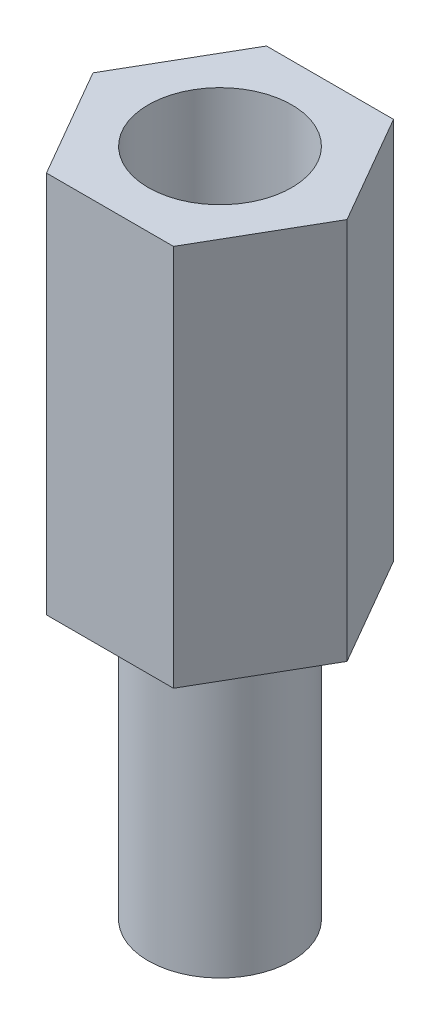
SolidWorks part; units mm, degrees
material "Brass"
ref_plane "Front Plane" through (0, 0, 0) normal (0, 0, 1) x (1, 0, 0)
ref_plane "Top Plane" through (0, 0, 0) normal (0, 1, 0) x (1, 0, 0)
ref_plane "Right Plane" through (0, 0, 0) normal (1, 0, 0) x (0, 0, -1)
sketch "Sketch1" plane through (0, 0, 0) normal (0, 1, 0) x (1, 0, 0)
  line L1 (2.6558, 0) -> (1.3279, 2.3)
  line L2 (1.3279, 2.3) -> (-1.3279, 2.3)
  line L3 (-1.3279, 2.3) -> (-2.6558, 0)
  line L4 (-2.6558, 0) -> (-1.3279, -2.3)
  line L5 (-1.3279, -2.3) -> (1.3279, -2.3)
  line L6 (1.3279, -2.3) -> (2.6558, 0)
  circle A0 centre (0, 0) radius 2.3 construction
  point P1 (0, 0)
  point P10 (0, 0)
  dimension "D1" = 4.6
extrude "HEX PART" add sketch "Sketch1" along normal blind 8
sketch "Sketch2" plane through (0, 0, 0) normal (0, 1, 0) x (1, 0, 0)
  circle A0 centre (0, 0) radius 1.5
  dimension "D1" = 3
extrude "THREAD" add sketch "Sketch2" against normal blind 6
sketch "Sketch3" plane through (0, 8, 0) normal (0, 1, 0) x (1, 0, 0)
  circle A0 centre (0, 0) radius 1.5
  dimension "D1" = 3
extrude "HEX THREAD" cut sketch "Sketch3" against normal blind 6
